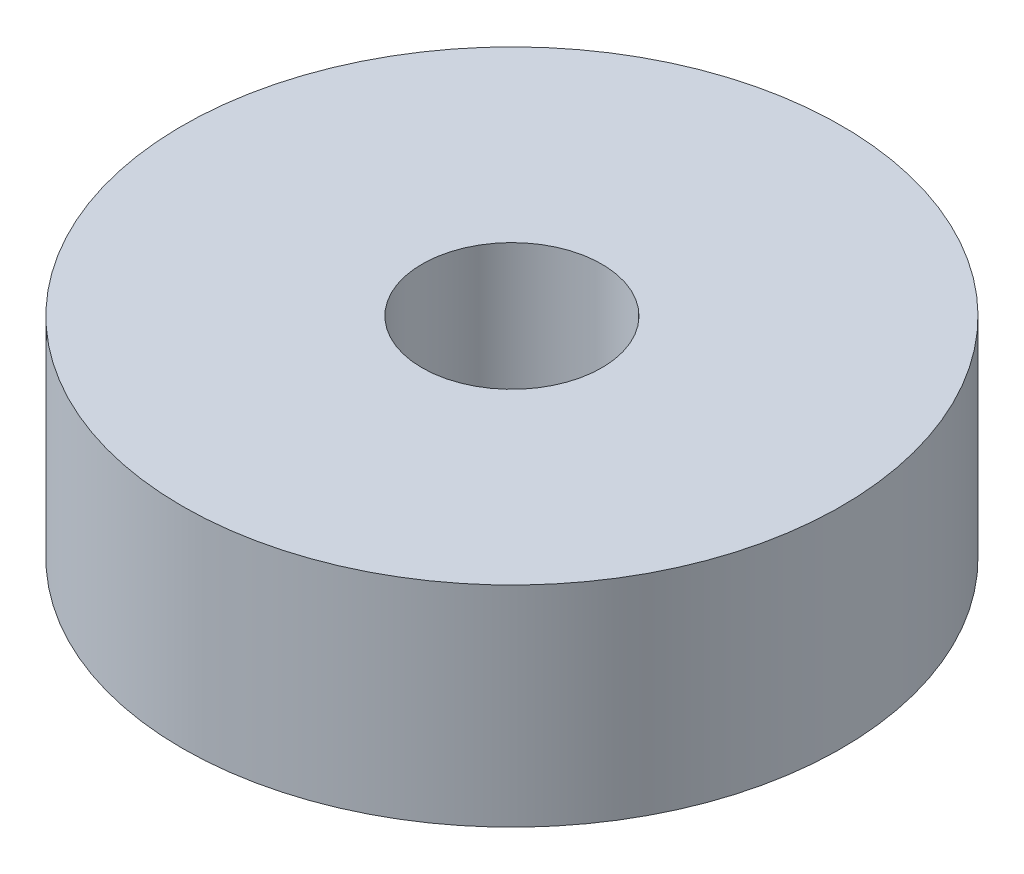
SolidWorks part; units mm, degrees
material "201 退火不锈钢 (SS)"
ref_plane "前视基准面" through (0, 0, 0) normal (0, 0, 1) x (1, 0, 0)
ref_plane "上视基准面" through (0, 0, 0) normal (0, 1, 0) x (1, 0, 0)
ref_plane "右视基准面" through (0, 0, 0) normal (1, 0, 0) x (0, 0, -1)
other "Configuration Table"
sketch "草图1" plane through (0, 0, 0) normal (0, 1, 0) x (1, 0, 0)
  circle A0 centre (0, 0) radius 3
  circle A1 centre (0, 0) radius 11
  dimension "D1" = 22
  dimension "D2" = 6
extrude "凸台-拉伸1" add sketch "草图1" along normal blind 7
